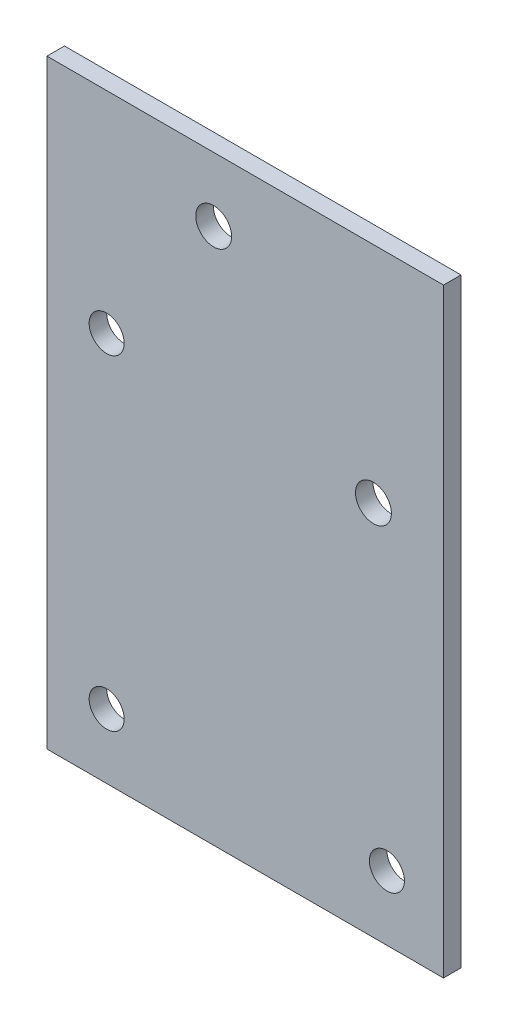
SolidWorks part; units mm, degrees
ref_plane "Front Plane" through (0, 0, 0) normal (0, 0, 1) x (1, 0, 0)
ref_plane "Top Plane" through (0, 0, 0) normal (0, 1, 0) x (1, 0, 0)
ref_plane "Right Plane" through (0, 0, 0) normal (1, 0, 0) x (0, 0, -1)
sketch "Sketch1" plane through (0, 0, 0) normal (0, 0, 1) x (1, 0, 0)
  line L1 (-15.1447, 165.1875) -> (-87.0132, 165.1875)
  line L2 (-15.1447, 165.1875) -> (-15.1447, 273.9571)
  line L3 (-15.1447, 273.9571) -> (-87.0132, 273.9571)
  line L4 (-87.0132, 165.1875) -> (-87.0132, 273.9571)
  line L5 (-44.1007, 246.1046) -> (-69.5007, 246.1046) construction
  line L6 (-44.1007, 246.1046) -> (-44.1007, 220.7046) construction
  circle A1 centre (-25.4, 176.8929) radius 3.175
  circle A2 centre (-76.2, 176.8929) radius 3.175
  circle A3 centre (-27.8447, 233.4046) radius 3.2512
  circle A4 centre (-56.8007, 262.3606) radius 3.2512
  circle A5 centre (-76.2, 235.8571) radius 3.175
  dimension "D2" = 6.35
  dimension "D3" = 6.35
  dimension "D1" = 6.35
  dimension "D12" = 6.5024
  dimension "D13" = 6.5024
  dimension "D4" = 10.8132
  dimension "D5" = 11.7054
  dimension "D6" = 38.1
  dimension "D8" = 12.7
  dimension "D9" = 12.7
  dimension "D10" = 16.256
  dimension "D11" = 12.7
  dimension "D7" = 16.256
extrude "Boss-Extrude1" add sketch "Sketch1" along normal blind 3.175
equation "\"80/20 to Center Hole\"= .64in"
equation "\"80/20 from Edge\"= 0.5in"
equation "\"D8@Sketch1\"=\"80/20 from Edge\""
equation "\"D7@Sketch1\"=\"80/20 to Center Hole\""
